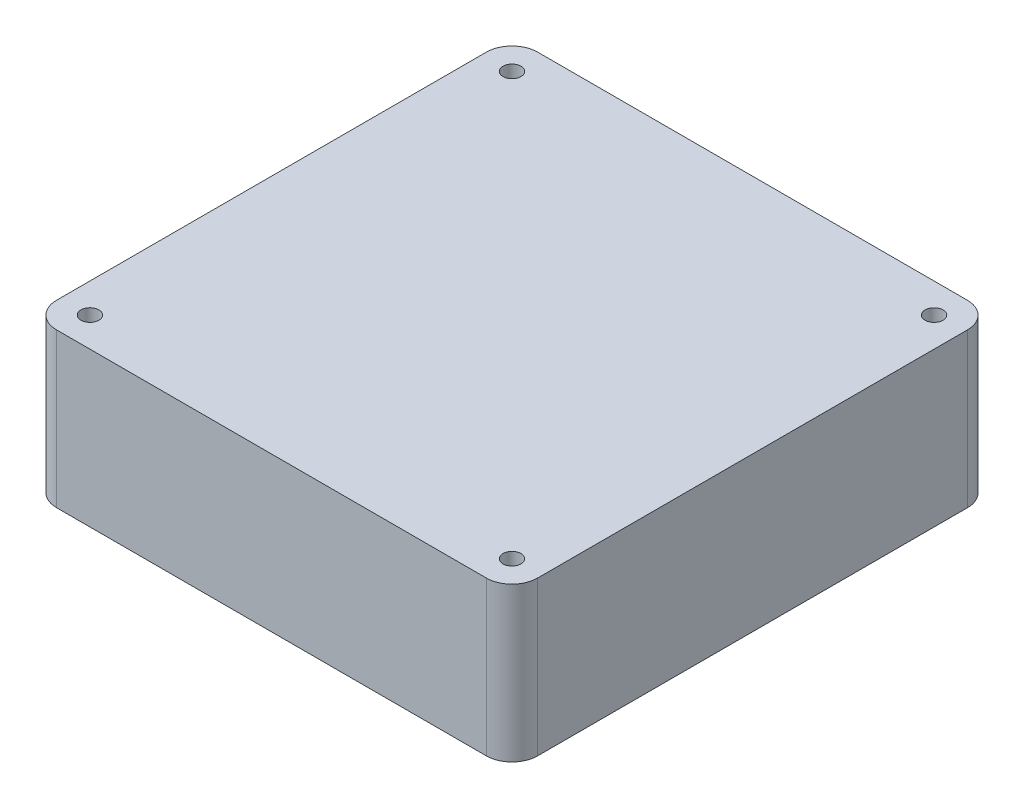
SolidWorks part; units mm, degrees
ref_plane "Front Plane" through (0, 0, 0) normal (0, 0, 1) x (1, 0, 0)
ref_plane "Top Plane" through (0, 0, 0) normal (0, 1, 0) x (1, 0, 0)
ref_plane "Right Plane" through (0, 0, 0) normal (1, 0, 0) x (0, 0, -1)
sketch "Sketch1" plane through (0, 0, 0) normal (0, 1, 0) x (1, 0, 0)
  line B0 (53.1459, -59.5027) -> (-53.1531, -59.4963)
  line B1 (59.4963, -53.1531) -> (59.5027, 53.1459)
  line B2 (53.1531, 59.4963) -> (-53.1459, 59.5027)
  line B3 (-59.5027, -53.1459) -> (-59.4963, 53.1531)
  circle B4 centre (-52.1939, 52.2001) radius 2.2225
  circle B5 centre (52.2001, 52.1939) radius 2.2225
  circle B6 centre (52.1939, -52.2001) radius 2.2225
  circle B7 centre (-52.2001, -52.1939) radius 2.2225
  arc B8 (-53.1531, -59.4963) -> (-59.5027, -53.1459) centre (-53.1527, -53.1463) cw
  arc B9 (53.1459, -59.5027) -> (59.4963, -53.1531) centre (53.1463, -53.1527) ccw
  arc B10 (59.5027, 53.1459) -> (53.1531, 59.4963) centre (53.1527, 53.1463) ccw
  arc B11 (-53.1459, 59.5027) -> (-59.4963, 53.1531) centre (-53.1463, 53.1527) ccw
sketch_block_instance "Large Kit Fan-1"
sketch_block "Large Kit Fan" parameters "D3"=4.445, "D4"=6.35, "D1"=118.999, "D2"=5.08
extrude "Boss-Extrude1" add sketch "Sketch1" along normal blind 38.1
